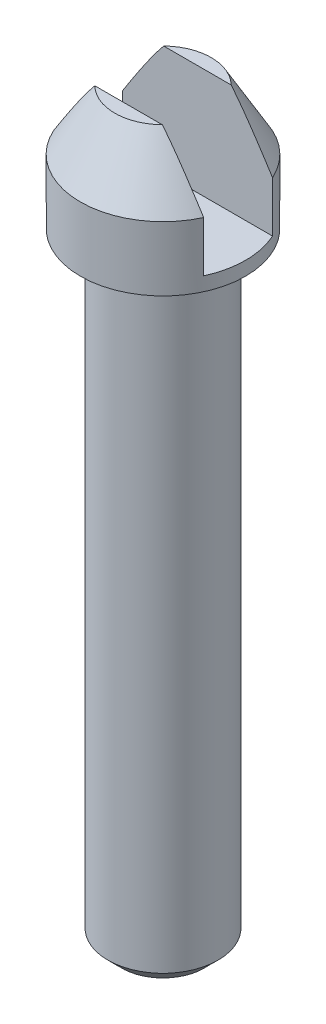
SolidWorks part; units mm, degrees
material "1.4301 (X5CrNi18-10)"
ref_plane "Vorne" through (0, 0, 0) normal (0, 0, 1) x (1, 0, 0)
ref_plane "Oben" through (0, 0, 0) normal (0, 1, 0) x (1, 0, 0)
ref_plane "Rechts" through (0, 0, 0) normal (1, 0, 0) x (0, 0, -1)
sketch "Skizze1" plane through (0, 0, 0) normal (0, 0, 1) x (1, 0, 0)
  line L0 (0, 0) -> (0, -29.3793) construction
  line L1 (0, 0) -> (0, 54)
  line L2 (0, 54) -> (-3.5, 54)
  line L3 (-3.5, 54) -> (-6, 49.6699)
  line L4 (-6, 49.6699) -> (-6, 45)
  line L5 (-6, 45) -> (-4, 45)
  line L6 (-4, 45) -> (-4, 0)
  line L7 (-4, 0) -> (0, 0)
  point P3 (-4, 56)
  point P10 (-6, 51.1858)
  dimension "D1" = 54
  dimension "D2" = 8
  dimension "D3" = 12
  dimension "D4" = 30
  dimension "D5" = 45
  dimension "D6" = 3.5
revolve "Rotation1" add sketch "Skizze1" angle 360 about L0
cosmetic thread "Gewindedarstellung1" parameters "D1"=16, "D2"=6.619
sketch "Skizze2" plane through (0, 54, 0) normal (0, 1, 0) x (1, 0, 0)
  line L1 (-7, 2.5) -> (7, 2.5)
  line L2 (-7, 2.5) -> (-7, -2.5)
  line L3 (-7, -2.5) -> (7, -2.5)
  line L4 (7, 2.5) -> (7, -2.5)
  point P4 (7, 0)
  point P6 (0, 2.5)
  dimension "D1" = 14
  dimension "D2" = 5
extrude "Schnitt-Linear austragen1" cut sketch "Skizze2" against normal blind 8
chamfer "Fase1" distance 1 angle 45 1 edges at (0, 0, 4)
